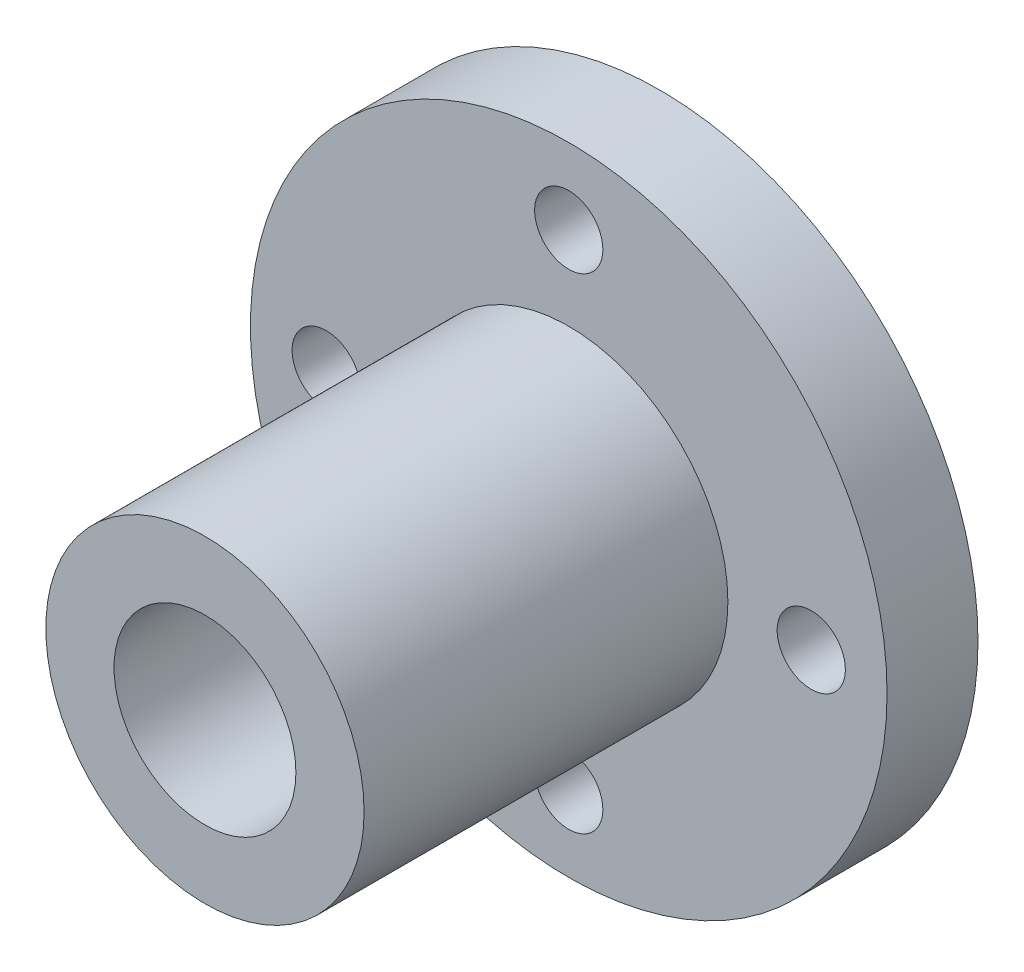
SolidWorks part; units mm, degrees
ref_plane "Front Plane" through (0, 0, 0) normal (0, 0, 1) x (1, 0, 0)
ref_plane "Top Plane" through (0, 0, 0) normal (0, 1, 0) x (1, 0, 0)
ref_plane "Right Plane" through (0, 0, 0) normal (1, 0, 0) x (0, 0, -1)
sketch "Sketch1" plane through (0, 0, 0) normal (0, 0, 1) x (1, 0, 0)
  circle A0 centre (0, 0) radius 21
  dimension "D1" = 42
extrude "Boss-Extrude1" add sketch "Sketch1" along normal blind 6
sketch "Sketch2" plane through (0, 0, 6) normal (0, 0, 1) x (1, 0, 0)
  circle A0 centre (0, 0) radius 10.5
  dimension "D1" = 21
extrude "Boss-Extrude2" add sketch "Sketch2" along normal blind 24
sketch "Sketch3" plane through (0, 0, 30) normal (0, 0, 1) x (1, 0, 0)
  circle A0 centre (0, 0) radius 6
  dimension "D1" = 12
extrude "Cut-Extrude1" cut sketch "Sketch3" against normal through all
sketch "Sketch4" plane through (0, 0, 6) normal (0, 0, 1) x (1, 0, 0)
  circle A1 centre (-16, 0) radius 2.25
  circle A2 centre (0, 16) radius 2.25
  circle A3 centre (16, 0) radius 2.25
  circle A4 centre (0, -16) radius 2.25
  point P14 (0, 0)
  dimension "D2" = 4.5
  dimension "D3" = 4
extrude "Cut-Extrude2" cut sketch "Sketch4" against normal through all
